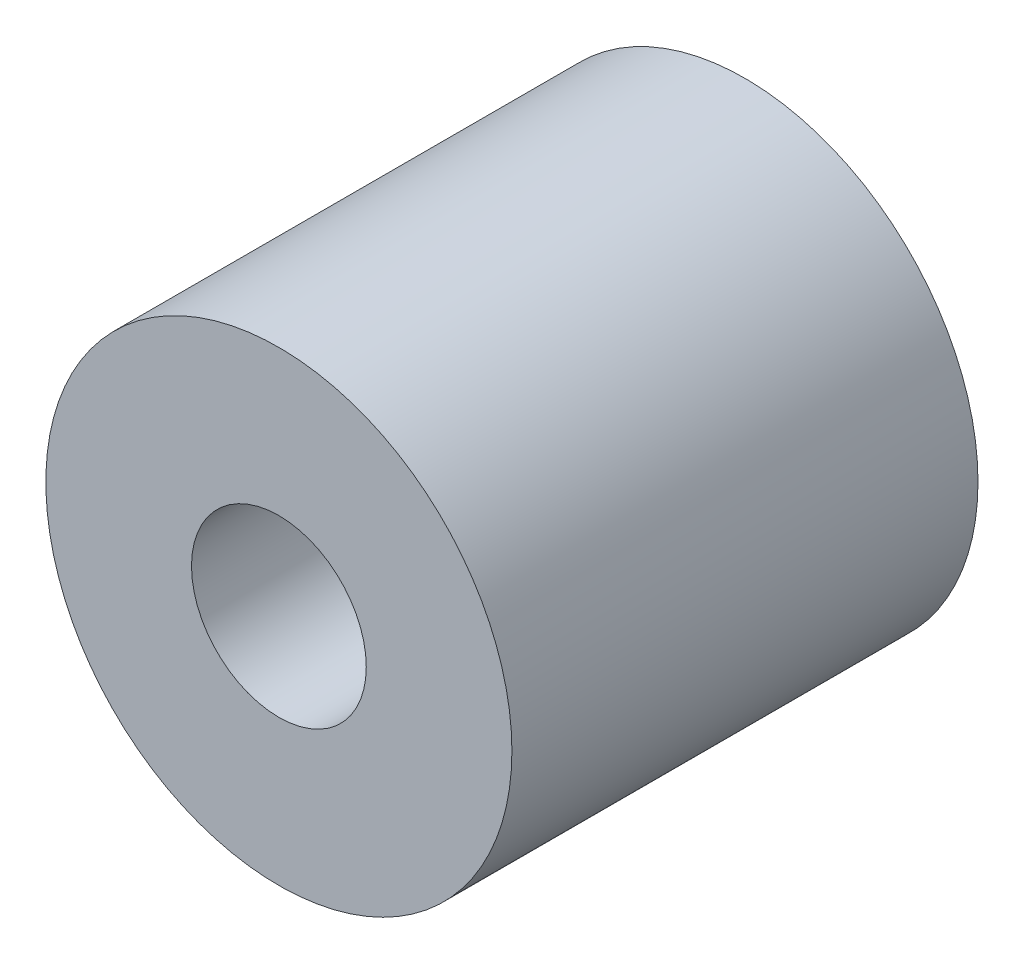
SolidWorks part; units mm, degrees
ref_plane "Front Plane" through (0, 0, 0) normal (0, 0, 1) x (1, 0, 0)
ref_plane "Top Plane" through (0, 0, 0) normal (0, 1, 0) x (1, 0, 0)
ref_plane "Right Plane" through (0, 0, 0) normal (1, 0, 0) x (0, 0, -1)
sketch "Sketch1" plane through (0, 0, 0) normal (0, 0, 1) x (1, 0, 0)
  circle A0 centre (0, 0) radius 4
  circle A1 centre (0, 0) radius 3
  dimension "D1" = 8
  dimension "D2" = 6
extrude "Boss-Extrude1" add sketch "Sketch1" along normal blind 8
sketch "Sketch2" plane through (0, 0, 8) normal (0, 0, 1) x (1, 0, 0)
  circle A0 centre (0, 0) radius 3
  circle A1 centre (0, 0) radius 1.5
  dimension "D1" = 3
extrude "Boss-Extrude2" add sketch "Sketch2" against normal offset from surface (5.5 mm away) 2.5 up to face at (4, 0, 0)
